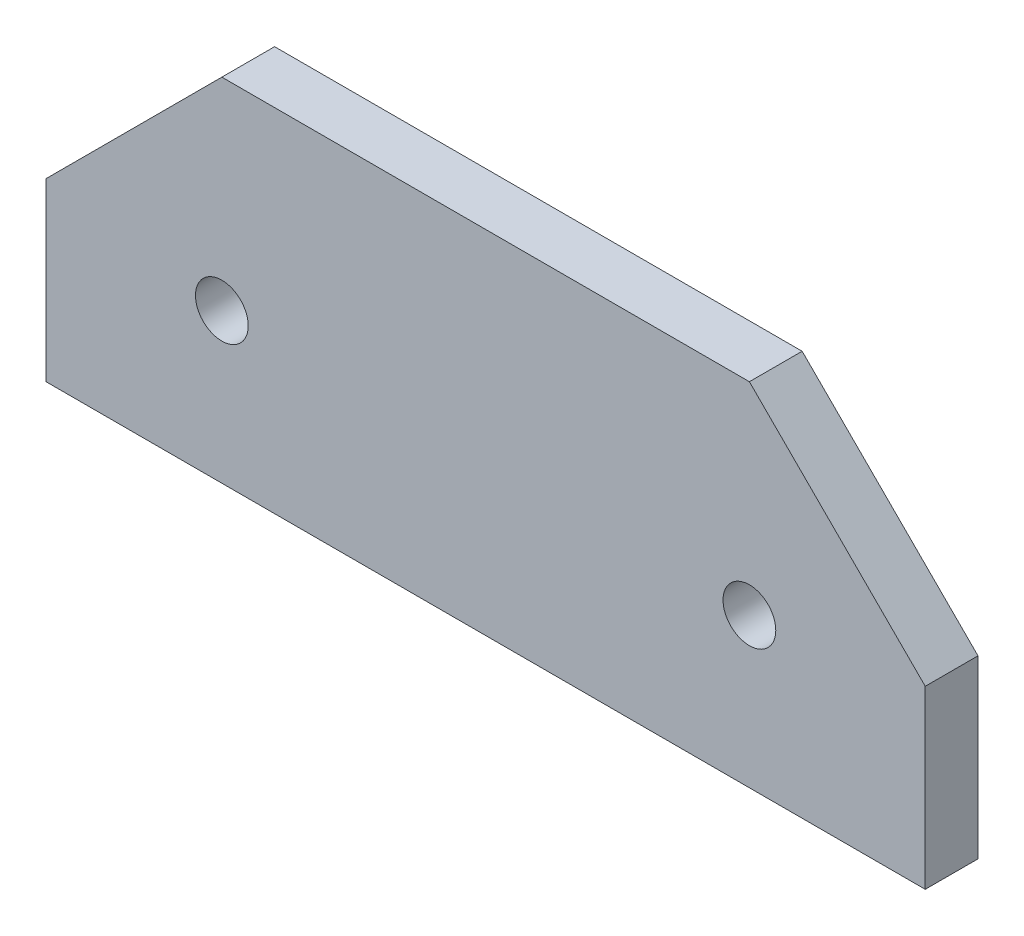
SolidWorks part; units mm, degrees
ref_plane "Alzado" through (0, 0, 0) normal (0, 0, 1) x (1, 0, 0)
ref_plane "Planta" through (0, 0, 0) normal (0, 1, 0) x (1, 0, 0)
ref_plane "Vista lateral" through (0, 0, 0) normal (1, 0, 0) x (0, 0, -1)
sketch "Croquis1" plane through (0, 0, 0) normal (0, 0, 1) x (1, 0, 0)
  line L0 (-25, 0) -> (-15, 10)
  line L1 (-25, -10) -> (25, -10)
  line L2 (-25, -10) -> (-25, 0)
  line L3 (-15, 10) -> (15, 10)
  line L4 (25, -10) -> (25, 0)
  line L5 (-25, -10) -> (25, 10) construction
  line L6 (-25, 10) -> (25, -10) construction
  line L7 (15, 10) -> (25, 0)
  line L9 (-15, 10) -> (15, 10) construction
  line L10 (-15, 10) -> (-15, -1.5) construction
  line L11 (-15, -1.5) -> (15, -1.5) construction
  line L12 (15, 10) -> (15, -1.5) construction
  circle A0 centre (-15, -1.5) radius 1.5
  circle A1 centre (15, -1.5) radius 1.5
  point P0 (0, 0)
  dimension "D1" = 50
  dimension "D2" = 20
  dimension "D3" = 11.5
extrude "Saliente-Extruir1" add sketch "Croquis1" along normal blind 3
